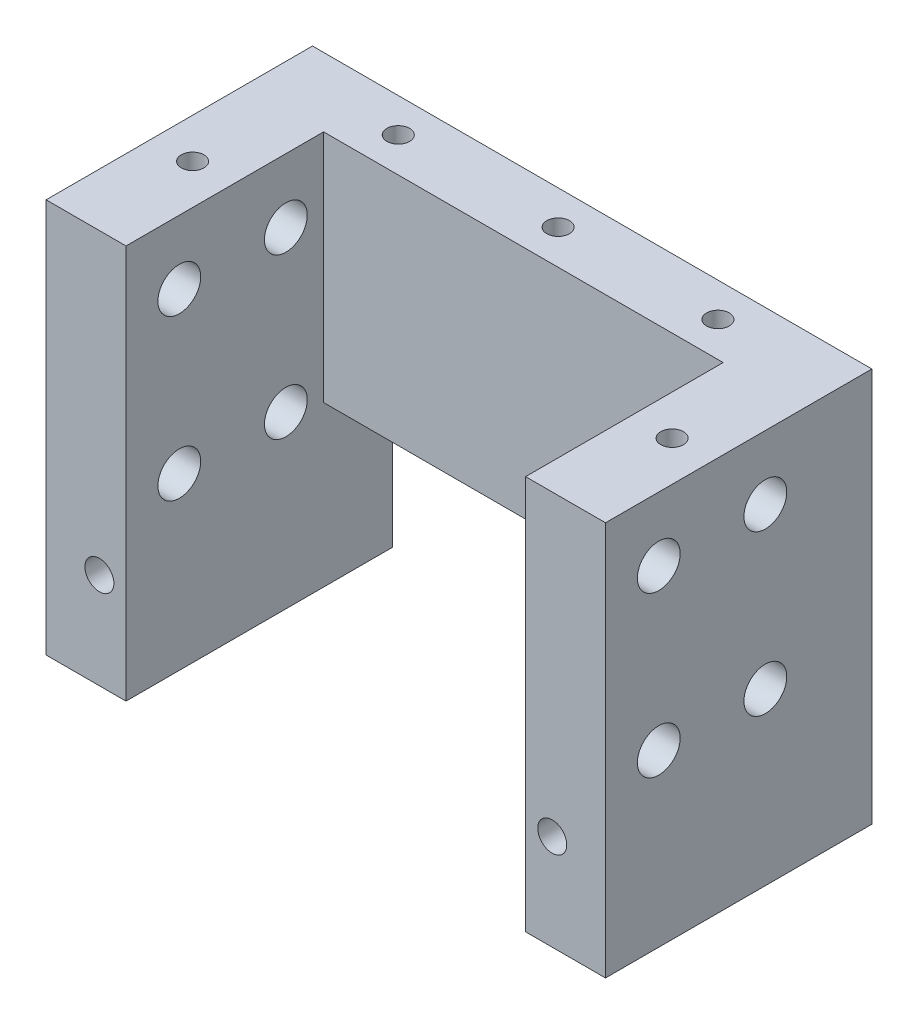
SolidWorks part; units mm, degrees
ref_plane "Front Plane" through (0, 0, 0) normal (0, 0, 1) x (1, 0, 0)
ref_plane "Top Plane" through (0, 0, 0) normal (0, 1, 0) x (1, 0, 0)
ref_plane "Right Plane" through (0, 0, 0) normal (1, 0, 0) x (0, 0, -1)
sketch "Sketch1" plane through (0, 0, 0) normal (0, 1, 0) x (1, 0, 0)
  line L1 (-33.3375, 15.875) -> (33.3375, 15.875)
  line L2 (-33.3375, 15.875) -> (-33.3375, -15.875)
  line L3 (-33.3375, -15.875) -> (33.3375, -15.875)
  line L4 (33.3375, 15.875) -> (33.3375, -15.875)
  dimension "D1" = 33.3375
  dimension "D2" = 33.3375
  dimension "D3" = 15.875
  dimension "D4" = 15.875
extrude "Boss-Extrude1" add sketch "Sketch1" along normal mid plane 46.99
sketch "Sketch2" plane through (0, 23.495, 0) normal (0, 1, 0) x (1, 0, 0)
  line L0 (-33.3375, -15.875) -> (33.3375, -15.875) construction
  line L1 (-23.8125, -15.875) -> (23.8125, -15.875)
  line L2 (-23.8125, -15.875) -> (-23.8125, 7.6753)
  line L3 (-23.8125, 7.6753) -> (23.8125, 7.6753)
  line L4 (23.8125, -15.875) -> (23.8125, 7.6753)
  line L5 (-33.3375, 15.875) -> (-33.3375, -15.875) construction
  line L6 (33.3375, -15.875) -> (33.3375, 15.875) construction
  dimension "D1" = 9.525
  dimension "D2" = 9.525
extrude "Cut-Extrude1" cut sketch "Sketch2" against normal up to next
sketch "Sketch3" plane through (0, 0, -15.875) normal (0, 0, -1) x (-1, 0, 0)
  line L0 (-33.3375, -23.495) -> (33.3375, -23.495) construction
  line L1 (-23.8125, -23.495) -> (23.8125, -23.495)
  line L2 (-23.8125, -23.495) -> (-23.8125, -4.445)
  line L3 (-23.8125, -4.445) -> (23.8125, -4.445)
  line L4 (23.8125, -23.495) -> (23.8125, -4.445)
  line L5 (-33.3375, 23.495) -> (-33.3375, -23.495) construction
  line L6 (33.3375, 23.495) -> (33.3375, -23.495) construction
  dimension "D1" = 9.525
  dimension "D2" = 9.525
  dimension "D3" = 19.05
extrude "Cut-Extrude2" cut sketch "Sketch3" against normal up to next
hole_wizard "1/4-20 Tapped Hole1" positions "Sketch5" profile "Sketch4" tap size "1/4-20" standard "ANSI Inch"
sketch "Sketch5" plane through (33.3375, 0, 0) normal (1, 0, 0) x (0, 0, -1)
  line L0 (-15.875, 23.495) -> (-15.875, -23.495) construction
  line L1 (-15.875, 23.495) -> (15.875, 23.495) construction
  point P0 (-9.525, 15.875)
  point P2 (3.175, 15.875)
  point P4 (3.175, -3.175)
  point P6 (-9.525, -3.175)
  dimension "D1" = 6.35
  dimension "D2" = 12.7
  dimension "D3" = 19.05
  dimension "D4" = 7.62
sketch "Sketch4" plane through (33.3375, 15.875, 9.525) normal (0, 1, 0) x (0, 0, -1)
  line L0 (0, 0) -> (0, 66.675)
  line L1 (0, 66.675) -> (2.5527, 66.675)
  line L2 (2.5527, 66.675) -> (2.5527, 0)
  line L5 (2.5527, 0) -> (0, 0)
  line L11 (0, -6.35) -> (0, 107.95) construction
  dimension "Thru Tap Drill Dia." = 5.1054
  dimension "Thru Tap Drill Depth" = 66.675
cosmetic thread "Hole Thread1" parameters "D2"=6.35
cosmetic thread "Hole Thread2" parameters "D2"=6.35
cosmetic thread "Hole Thread3" parameters "D2"=6.35
cosmetic thread "Hole Thread4" parameters "D2"=6.35
mirror "Mirror1" about plane through (0, 0, 0) normal (1, 0, 0) of "1/4-20 Tapped Hole1"
hole_wizard "#8-32 Tapped Hole1" positions "Sketch7" profile "Sketch6" tap size "#8-32" standard "ANSI Inch"
sketch "Sketch7" plane through (0, 0, 15.875) normal (0, 0, 1) x (1, 0, 0)
  line L0 (23.8125, -23.495) -> (33.3375, -23.495) construction
  line L3 (23.8125, -23.495) -> (23.8125, 23.495) construction
  line L4 (-23.8125, -23.495) -> (-23.8125, 23.495) construction
  point P0 (-26.9875, -12.065)
  point P2 (26.9875, -12.065)
  dimension "D1" = 11.43
  dimension "D2" = 3.175
  dimension "D3" = 3.175
sketch "Sketch6" plane through (-26.9875, -12.065, 15.875) normal (1, 0, 0) x (0, -1, 0)
  line L0 (0, 0) -> (0, 13.4838)
  line L1 (0, 13.4838) -> (1.7272, 12.446)
  line L2 (1.7272, 12.446) -> (1.7272, 0)
  line L5 (1.7272, 0) -> (0, 0)
  line L10 (0, 13.4838) -> (-1.7272, 12.446) construction
  line L11 (0, -6.35) -> (0, 107.95) construction
  dimension "Tap Drill Dia." = 3.4544
  dimension "Tap Drill Depth" = 12.446
  dimension "Drill Angle" = 118
cosmetic thread "Hole Thread5" parameters "D1"=8.382, "D2"=4.1656
cosmetic thread "Hole Thread6" parameters "D1"=8.382, "D2"=4.1656
hole_wizard "#6-32 Tapped Hole1" positions "Sketch9" profile "Sketch8" tap size "#6-32" standard "ANSI Inch"
sketch "Sketch9" plane through (0, 23.495, 0) normal (0, 1, 0) x (1, 0, 0)
  line L0 (33.3375, 15.875) -> (-33.3375, 15.875) construction
  line L1 (33.3375, -15.875) -> (33.3375, 15.875) construction
  line L2 (-33.3375, 15.875) -> (-33.3375, -15.875) construction
  line L3 (23.8125, -15.875) -> (33.3375, -15.875) construction
  point P0 (0, 11.811)
  point P2 (19.05, 11.811)
  point P4 (-19.05, 11.811)
  point P9 (-28.575, -3.175)
  point P11 (28.575, -3.175)
  dimension "D1" = 4.064
  dimension "D2" = 19.05
  dimension "D3" = 19.05
  dimension "D4" = 4.7625
  dimension "D5" = 4.7625
  dimension "D6" = 12.7
sketch "Sketch8" plane through (0, 23.495, -11.811) normal (1, 0, 0) x (0, 0, 1)
  line L0 (0, 0) -> (0, 14.5287)
  line L1 (0, 14.5287) -> (1.3525, 13.716)
  line L2 (1.3525, 13.716) -> (1.3525, 0)
  line L5 (1.3525, 0) -> (0, 0)
  line L10 (0, 14.5287) -> (-1.3526, 13.716) construction
  line L11 (0, -6.35) -> (0, 107.95) construction
  dimension "Tap Drill Dia." = 2.7051
  dimension "Tap Drill Depth" = 13.716
  dimension "Drill Angle" = 118
cosmetic thread "Hole Thread7" parameters "D1"=9.652, "D2"=3.5052
cosmetic thread "Hole Thread8" parameters "D1"=9.652, "D2"=3.5052
cosmetic thread "Hole Thread9" parameters "D1"=9.652, "D2"=3.5052
cosmetic thread "Hole Thread10" parameters "D1"=9.652, "D2"=3.5052
cosmetic thread "Hole Thread11" parameters "D1"=9.652, "D2"=3.5052
